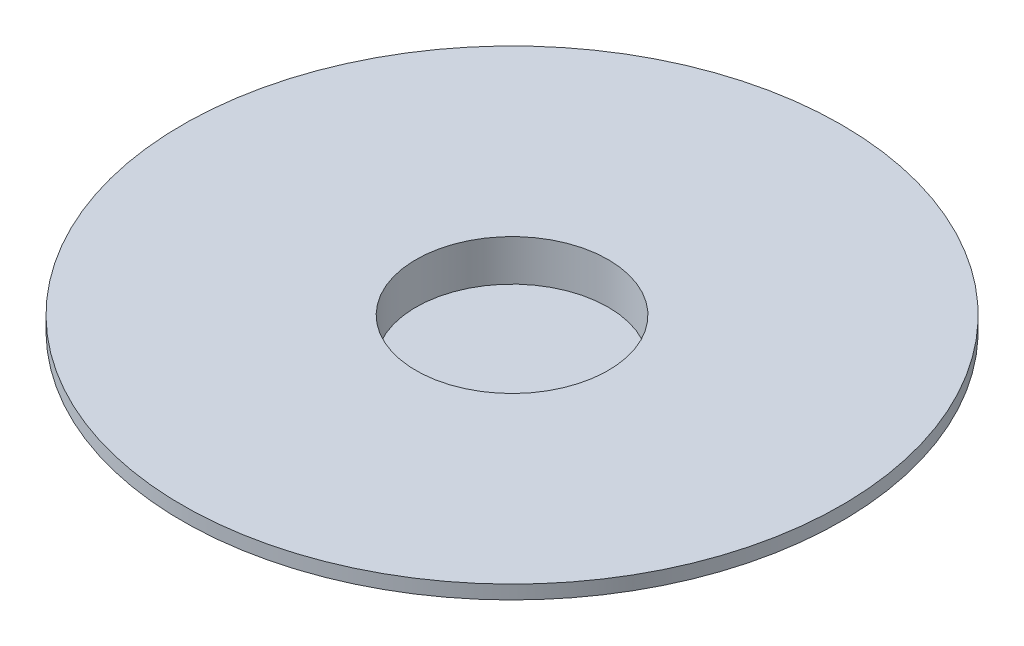
SolidWorks part; units mm, degrees
ref_plane "Спереди" through (0, 0, 0) normal (0, 0, 1) x (1, 0, 0)
ref_plane "Сверху" through (0, 0, 0) normal (0, 1, 0) x (1, 0, 0)
ref_plane "Справа" through (0, 0, 0) normal (1, 0, 0) x (0, 0, -1)
sketch "Эскиз1" plane through (0, 0, 0) normal (0, 0, 1) x (1, 0, 0)
  line L0 (0, 0) -> (-35, 0)
  line L1 (-35, 0) -> (-35, 15)
  line L4 (-40, -30) -> (0, -30)
  line L6 (0, -30) -> (0, 0)
  line L7 (-40, -30) -> (-40, 10)
  line L8 (-40, 10) -> (-120, 10)
  line L9 (-120, 10) -> (-120, 15)
  line L10 (-120, 15) -> (-35, 15)
  dimension "D1" = 120
  dimension "D2" = 40
  dimension "D3" = 5
  dimension "D4" = 30
  dimension "D5" = 35
  dimension "D6" = 10
revolve "Повернуть1" add sketch "Эскиз1" angle 360 about L6
sketch "Эскиз2" plane through (0, -30, 0) normal (0, -1, 0) x (1, 0, 0)
  line L0 (0, -40) -> (0, 40) construction
  line L1 (-40, 0) -> (40, 0) construction
  circle A0 centre (0, 0) radius 35
  circle A1 centre (0, 0) radius 40 construction
  point P9 (0, 0)
  point P10 (0, 0)
  dimension "D1" = 70
extrude "Вырез-Вытянуть1" cut sketch "Эскиз2" against normal blind 20
